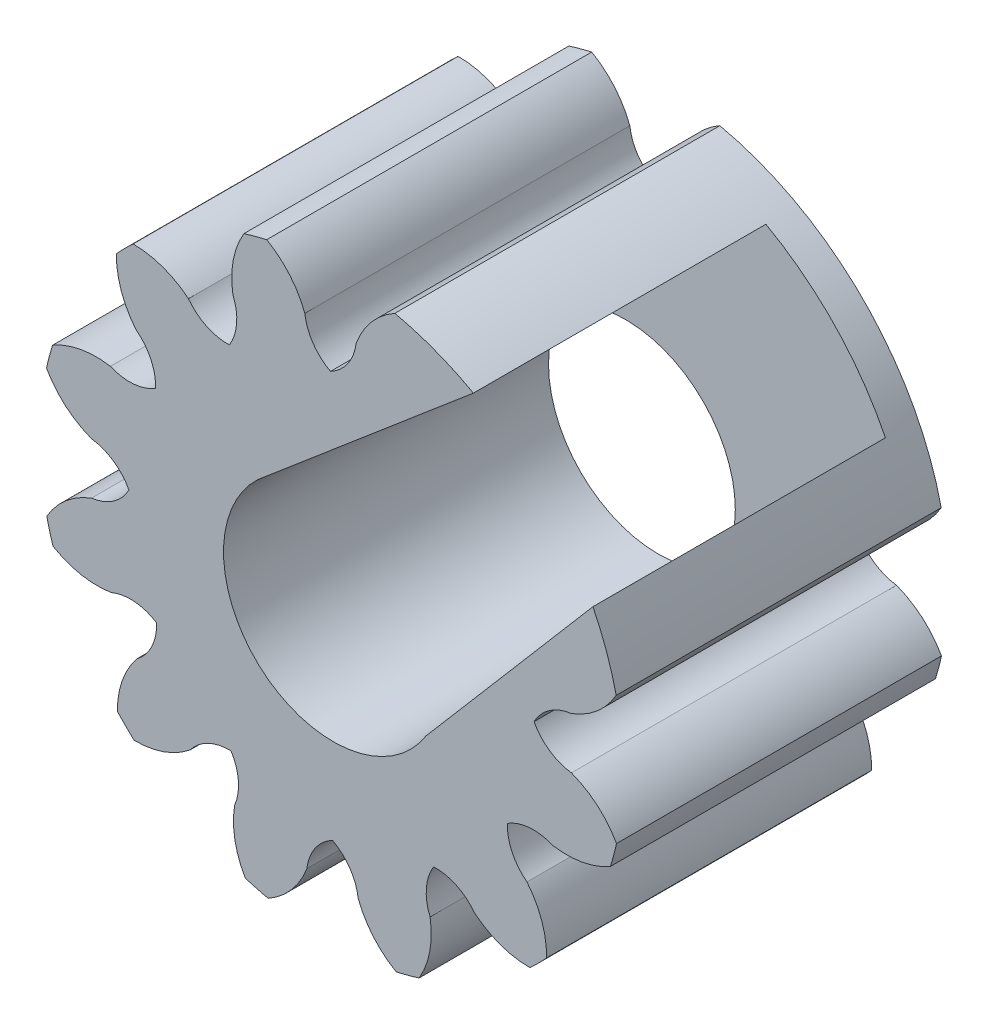
SolidWorks part; units mm, degrees
ref_plane "Front Plane" through (0, 0, 0) normal (0, 0, 1) x (1, 0, 0)
ref_plane "Top Plane" through (0, 0, 0) normal (0, 1, 0) x (1, 0, 0)
ref_plane "Right Plane" through (0, 0, 0) normal (1, 0, 0) x (0, 0, -1)
sketch "Sketch1" plane through (0, 0, 0) normal (0, 0, 1) x (1, 0, 0)
  circle A3 centre (0, 0) radius 8.9834
extrude "Boss-Extrude2" add sketch "Sketch1" against normal blind 10
sketch "Sketch2" plane through (0, 0, 0) normal (0, 0, 1) x (1, 0, 0)
  line L4 (-1.9748, 2.4771) -> (4.366, 7.8511)
  line L6 (2.911, -2.0089) -> (8.0441, 3.9993)
  arc A2 (-1.9748, 2.4771) -> (2.911, -2.0089) centre (0.051, -0.2202) ccw
  circle A3 centre (0, 0) radius 8.9834 construction
  arc A4 (4.366, 7.8511) -> (8.0441, 3.9993) centre (0, 0) cw
extrude "Cut-Extrude1" cut sketch "Sketch2" against normal blind 9
sketch "Sketch9" plane through (0, 0, 0) normal (0, 0, 1) x (1, 0, 0)
  circle A0 centre (0.051, -0.2202) radius 3.3733
extrude "Cut-Extrude4" cut sketch "Sketch9" against normal blind 10
sketch "Sketch10" plane through (0, 0, 0) normal (0, 0, 1) x (1, 0, 0)
  line L0 (-0.0306, -5.0091) -> (-0.0306, 10.9587) construction
  arc A0 (-0.0306, 6.2325) -> (0.7594, 7.3825) centre (-0.7394, 7.5658) ccw
  arc A1 (0.7594, 7.3825) -> (2.0694, 8.8325) centre (3.2502, 6.449) cw
  arc A2 (-0.0306, 6.2325) -> (-0.8206, 7.3825) centre (0.6782, 7.5658) cw
  arc A3 (-0.8206, 7.3825) -> (-2.1306, 8.8325) centre (-3.3114, 6.449) ccw
  arc A4 (-2.1306, 8.8325) -> (2.0694, 8.8325) centre (-0.0306, -5.0091) cw
  dimension "D1" = 2.66
  dimension "D2" = 1.51
  dimension "D3" = 1.45
  dimension "D4" = 1.31
  dimension "D5" = 1.15
  dimension "D6" = 0.79
extrude "Cut-Extrude5" cut sketch "Sketch10" against normal blind 10
pattern_circular "CirPattern2" count 10 every 30 about axis through (0, 0, 0) along (0, 0, 1) of "Cut-Extrude5"
